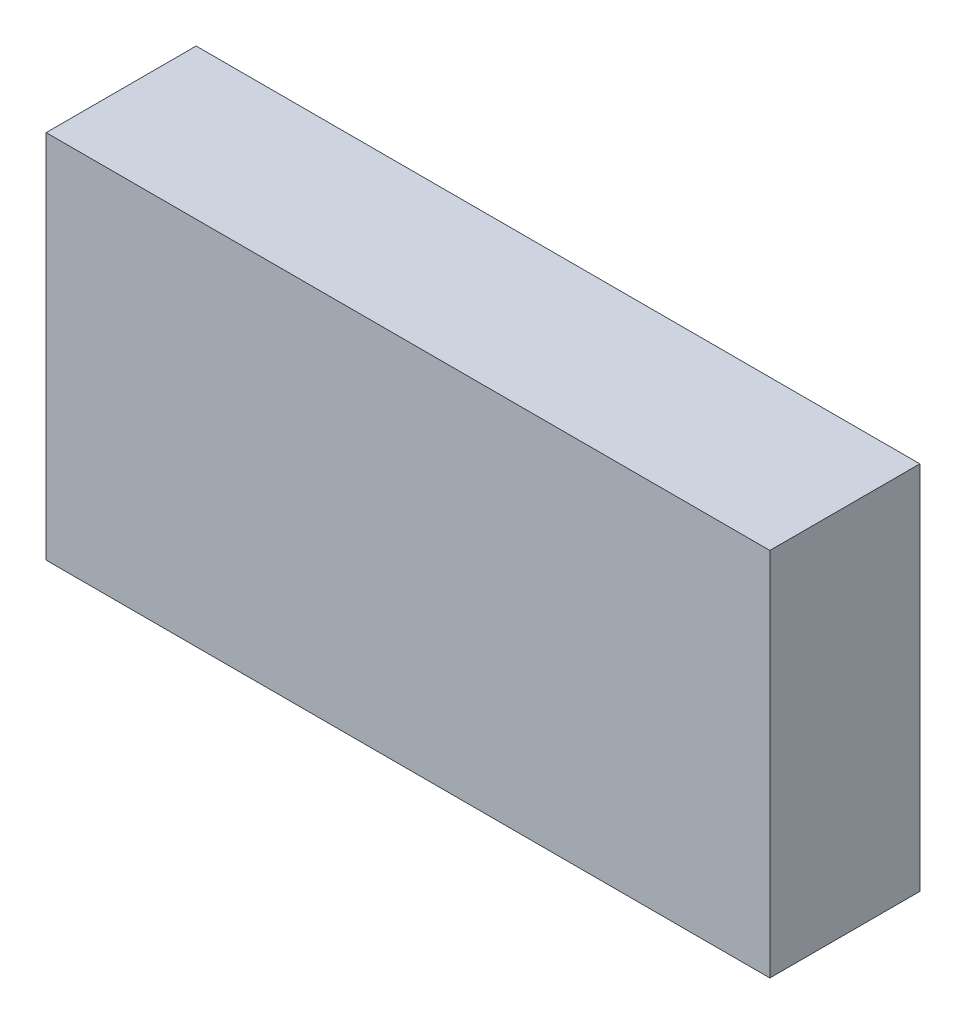
SolidWorks part; units mm, degrees
ref_plane "Front Plane" through (0, 0, 0) normal (0, 0, 1) x (1, 0, 0)
ref_plane "Top Plane" through (0, 0, 0) normal (0, 1, 0) x (1, 0, 0)
ref_plane "Right Plane" through (0, 0, 0) normal (1, 0, 0) x (0, 0, -1)
sketch "Sketch1" plane through (0, 0, 0) normal (0, 0, 1) x (1, 0, 0)
  line L1 (-35.22, 18.02) -> (35.22, 18.02)
  line L2 (-35.22, 18.02) -> (-35.22, -18.02)
  line L3 (-35.22, -18.02) -> (35.22, -18.02)
  line L4 (35.22, 18.02) -> (35.22, -18.02)
  line L5 (-35.22, 18.02) -> (35.22, -18.02) construction
  line L6 (-35.22, -18.02) -> (35.22, 18.02) construction
  point P0 (0, 0)
  dimension "D1" = 70.44
  dimension "D2" = 36.04
extrude "Boss-Extrude1" add sketch "Sketch1" along normal blind 14.6
